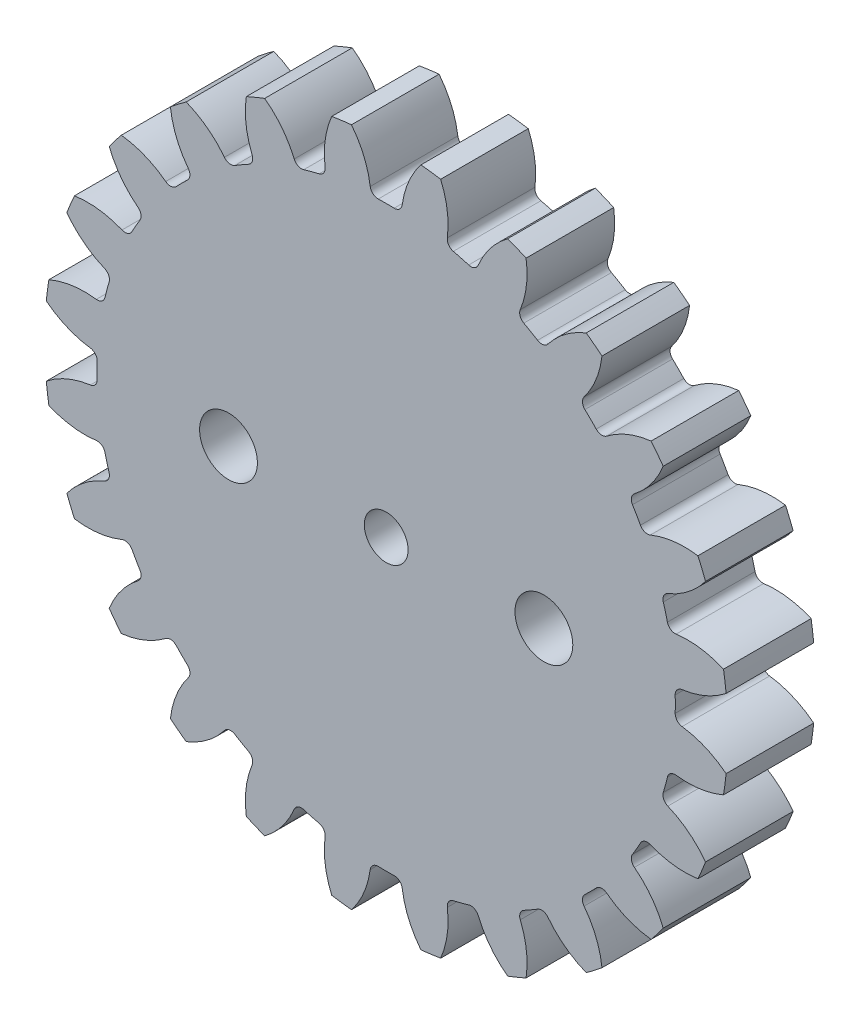
SolidWorks part; units mm, degrees
ref_plane "Front" through (0, 0, 0) normal (0, 0, 1) x (1, 0, 0)
ref_plane "Top" through (0, 0, 0) normal (0, 1, 0) x (1, 0, 0)
ref_plane "Right" through (0, 0, 0) normal (1, 0, 0) x (0, 0, -1)
sketch "Sketch1" plane through (0, 0, 0) normal (0, 0, 1) x (1, 0, 0)
  circle A0 centre (0, 0) radius 16.5
  circle A1 centre (0, 0) radius 19.5
  circle A2 centre (0, 0) radius 18
  dimension "D1" = 39
  dimension "D2" = 33
  dimension "D3" = 36
extrude "Boss-Extrude1" add sketch "Sketch1" along normal mid plane 5 contours A1
sketch "Sketch3" plane through (0, 0, 0) normal (0, 0, 1) x (1, 0, 0)
  line L0 (0, 0) -> (0, 19.5) construction
  line L1 (0, 0) -> (-0.8747, 16.4768) construction
  line L2 (-1.1773, 17.9615) -> (1.1773, 17.9615) construction
  line L3 (-1.7099, 19.4249) -> (0, 14.727) construction
  line L4 (0, 0) -> (2.5453, 19.3332) construction
  line L5 (1.1773, 17.9615) -> (3.5116, 17.6541) construction
  arc A0 (-0.8747, 16.4768) -> (0.8747, 16.4768) centre (0, 0) cw
  arc A4 (1.9816, 19.3991) -> (-1.9816, 19.3991) centre (0, 0) ccw
  circle A5 centre (0, 0) radius 19.5 construction
  arc A7 (-1.9816, 19.3991) -> (-0.8747, 16.4768) centre (-6.0045, 16.2045) cw
  arc A10 (1.9816, 19.3991) -> (0.8747, 16.4768) centre (6.0045, 16.2045) ccw
  circle A11 centre (0, 0) radius 16.5 construction
  circle A12 centre (0, 0) radius 18 construction
  dimension "D1" = 20
  dimension "D2" = 7.5
extrude "Cut-Extrude1" cut sketch "Sketch3" against normal through all both and the other way through all
fillet "Fillet2" radius 0.45 2 edges at (0.8747, 16.4768, 0) (-0.8747, 16.4768, 0)
pattern_circular "CirPattern1" count 24 over 360 about axis through (0, 0, 0) along (0, 0, 1) of "Cut-Extrude1", "Fillet2"
sketch "Sketch4" plane through (0, 0, 0) normal (0, 0, 1) x (1, 0, 0)
  circle A0 centre (0, 0) radius 1.25
  dimension "D1" = 2.5
extrude "Through_Center_Hole" cut sketch "Sketch4" against normal through all both and the other way through all
sketch "Sketch5" plane through (0, 0, 0) normal (0, 0, 1) x (1, 0, 0)
  line L0 (-9, 0) -> (9, 0) construction
  circle A0 centre (9, 0) radius 1.65
  circle A1 centre (-9, 0) radius 1.65
  dimension "D2" = 3.3
  dimension "D1" = 18
extrude "To_Knuckle_Mount" cut sketch "Sketch5" against normal through all both and the other way through all
equation "\"od\"= 39'outside diameter"
equation "\"n\"= 24'number of teeth"
equation "\"m\"= \"od\" / ( \"n\" + 2 )'module"
equation "\"p\"= \"m\" * pi'pitch"
equation "\"d\"= \"m\" * \"n\"'primitive diameter"
equation "\"da\"= \"d\" + 2 * \"m\"'head diamater"
equation "\"df\"= \"d\" - 2 * \"m\"'foot diameter"
equation "\"D1@Sketch1\"=\"od\""
equation "\"D2@Sketch1\"=\"df\""
equation "\"D3@Sketch1\"=\"d\""
equation "\"D2@Sketch3\"=180/\"n\""
equation "\"D1@Fillet2\"=.3*\"m\""
equation "\"D1@CirPattern1\"=\"n\""
